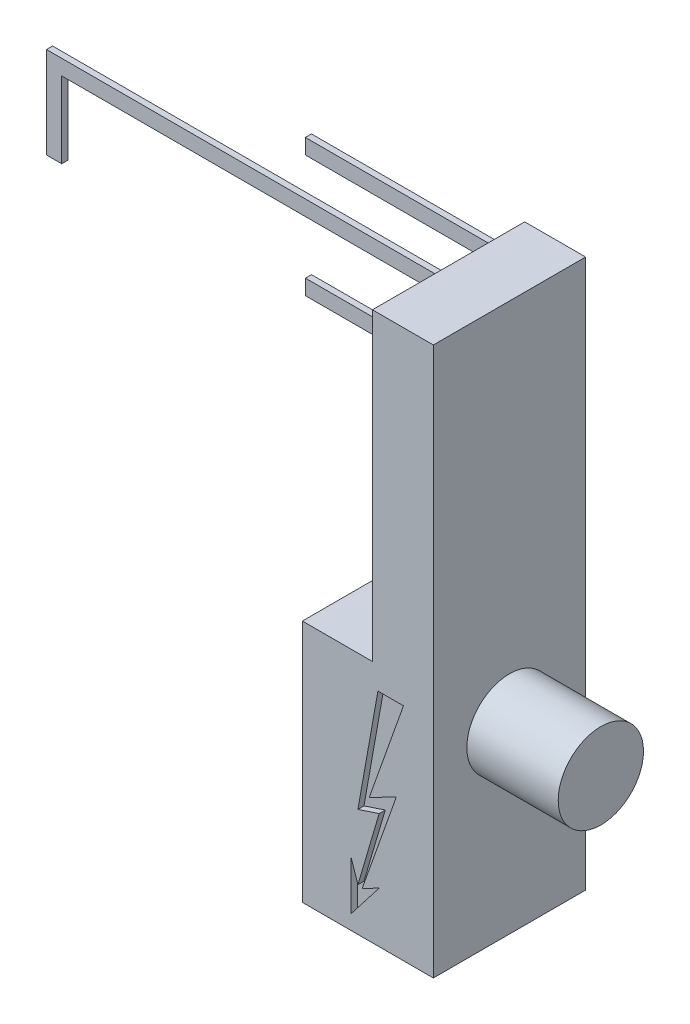
SolidWorks part; units mm, degrees
ref_plane "Front Plane" through (0, 0, 0) normal (0, 0, 1) x (1, 0, 0)
ref_plane "Top Plane" through (0, 0, 0) normal (0, 1, 0) x (1, 0, 0)
ref_plane "Right Plane" through (0, 0, 0) normal (1, 0, 0) x (0, 0, -1)
sketch "Sketch1" plane through (0, 0, 0) normal (0, 0, 1) x (1, 0, 0)
  line L0 (-15, -45) -> (6.5, -45)
  line L2 (6.5, -45) -> (6.5, 45)
  line L3 (6.5, 45) -> (-3.5, 45)
  line L4 (-3.5, -5) -> (-3.5, 45)
  line L9 (-3.5, -5) -> (-15, -5)
  line L10 (-15, -45) -> (-15, -5)
  point P0 (0, 0)
  point P4 (0, 0)
  dimension "D1" = 10
  dimension "D2" = 90
  dimension "D3" = 21.5
  dimension "D4" = 40
  dimension "D5" = 11.5
extrude "Boss-Extrude1" add sketch "Sketch1" along normal mid plane 25
sketch "Sketch2" plane through (0, 0, 12.5) normal (0, 0, 1) x (1, 0, 0)
  line L0 (-2.5976, -8.7539) -> (-5.8817, -27.2271)
  line L1 (-5.8817, -27.2271) -> (-2.3877, -26.0624)
  line L2 (-2.3877, -26.0624) -> (-5.8817, -37.9209)
  line L3 (-5.8817, -37.9209) -> (-6.985, -34.6112)
  line L4 (-6.985, -34.6112) -> (-6.985, -42.5971)
  line L5 (-6.985, -42.5971) -> (-2.3877, -36.661)
  line L6 (-2.3877, -36.661) -> (-5.1863, -38.1258)
  line L7 (-5.1863, -38.1258) -> (0.4361, -22.2791)
  line L8 (0.4361, -22.2791) -> (-4.0288, -24.6162)
  line L9 (-4.0288, -24.6162) -> (1.5991, -8.7539)
  line L10 (1.5991, -8.7539) -> (-2.5976, -8.7539)
  point P2 (0, 0)
extrude "Cut-Extrude1" cut sketch "Sketch2" against normal blind 1 contours L10 L0 L1 L2 L3 L4 L5 L6 L7 L8 L9
ref_plane "Plane1" through (0, 0, -12.5) normal (0, 0, -1) x (-1, 0, 0)
sketch "Sketch4" plane through (0, 0, -12.5) normal (0, 0, -1) x (-1, 0, 0)
  line L0 (3.5, 40) -> (38.5, 40)
  line L1 (3.5, 45) -> (3.5, -5) construction
  line L2 (38.5, 40) -> (38.5, 37.5)
  line L3 (38.5, 37.5) -> (3.5, 37.5)
  line L4 (3.5, 37.5) -> (3.5, 40)
  line L5 (-6.5, 45) -> (3.5, 45) construction
  line L6 (38.5, 17.5) -> (3.5, 17.5)
  line L7 (3.5, 20) -> (38.5, 20)
  line L8 (38.5, 20) -> (38.5, 17.5)
  line L9 (3.5, 17.5) -> (3.5, 20)
  line L10 (3.5, 45) -> (3.5, -5) construction
  line L11 (3.5, 31.25) -> (78.5, 31.25)
  line L12 (3.5, 31.25) -> (3.5, 28.75)
  line L13 (3.5, 28.75) -> (78.5, 28.75)
  line L15 (-6.5, 45) -> (3.5, 45) construction
  line L16 (3.5, 45) -> (3.5, -5) construction
  line L17 (78.5, 31.25) -> (81, 31.25)
  line L18 (78.5, 28.75) -> (78.5, 16.25)
  line L19 (78.5, 16.25) -> (81, 16.25)
  line L20 (81, 31.25) -> (81, 16.25)
  point P18 (3.5, 30)
  dimension "D1" = 2.5
  dimension "D2" = 35
  dimension "D3" = 5
  dimension "D4" = 75
  dimension "D5" = 2.5
  dimension "D6" = 15
  dimension "D7" = 2.5
  dimension "D8" = 15
extrude "Boss-Extrude2" add sketch "Sketch4" against normal blind 1 separate body
sketch "Sketch6" plane through (6.5, 0, 0) normal (1, 0, 0) x (0, 0, -1)
  line L1 (-12.5, -45) -> (12.5, -45) construction
  circle A0 centre (0, -15) radius 7
  dimension "D1" = 14
  dimension "D2" = 30
extrude "Boss-Extrude3" add sketch "Sketch6" along normal blind 15
